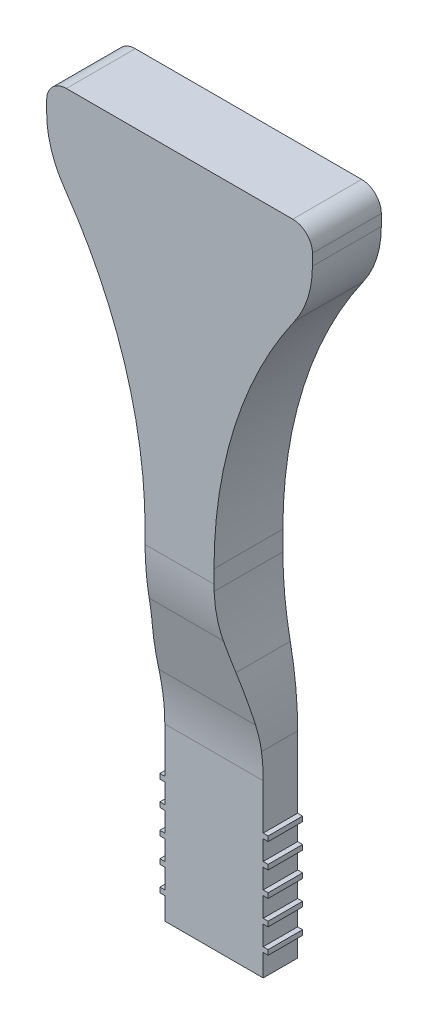
SolidWorks part; units mm, degrees
ref_plane "Front Plane" through (0, 0, 0) normal (0, 0, 1) x (1, 0, 0)
ref_plane "Top Plane" through (0, 0, 0) normal (0, 1, 0) x (1, 0, 0)
ref_plane "Right Plane" through (0, 0, 0) normal (1, 0, 0) x (0, 0, -1)
sketch "Sketch1" plane through (0, 0, 0) normal (0, 0, 1) x (1, 0, 0)
  line L0 (-4.25, -42.6429) -> (4.25, -42.6429) construction
  line L1 (-5, -50.1429) -> (-5, -70.1429)
  line L2 (-5, -70.1429) -> (5, -70.1429)
  line L3 (5, -70.1429) -> (5, -50.1429)
  line L5 (-13.5, -1.5201) -> (-13.5, -0.3772)
  line L6 (-11.5, 1.6228) -> (11.5, 1.6228)
  line L7 (13.5, -0.3772) -> (13.5, -1.5201)
  line L13 (3.5, -33.1429) -> (3.5, -35.1429)
  line L14 (3.5, -35.1429) -> (-3.5, -35.1429) construction
  line L15 (-3.5, -35.1429) -> (-3.5, -33.1429)
  line L22 (-3.5, -33.1429) -> (3.5, -33.1429) construction
  line L23 (-11.6818, -7.2697) -> (11.6818, -7.2697) construction
  line L24 (0, 3.6228) -> (0, -7.2697) construction
  line L25 (12.7, 3.6228) -> (-12.7, 3.6228) construction
  line L26 (-5, -50.1429) -> (5, -50.1429) construction
  line L27 (0, -35.1429) -> (0, -42.6429) construction
  line L28 (0, -42.6429) -> (0, -50.1429) construction
  arc A0 (-3.5, -35.1429) -> (-4.25, -42.6429) centre (-41.375, -35.1429) cw
  arc A1 (3.5, -35.1429) -> (4.25, -42.6429) centre (41.375, -35.1429) ccw
  arc A2 (11.7818, -7.1268) -> (3.7267, -29.625) centre (48.6, -33) ccw construction
  arc A3 (11.7818, -7.1268) -> (3.7267, -29.625) centre (48.6, -33) ccw construction
  arc A4 (-4.25, -42.6429) -> (-5, -50.1429) centre (32.875, -50.1429) ccw
  arc A5 (4.25, -42.6429) -> (5, -50.1429) centre (-32.875, -50.1429) cw
  arc A24 (13.5, -1.5201) -> (11.6818, -7.2697) centre (3.5, -1.5201) cw
  arc A25 (-13.5, -1.5201) -> (-11.6818, -7.2697) centre (-3.5, -1.5201) ccw
  arc A26 (-11.6818, -7.2697) -> (-3.5, -33.1429) centre (-48.5, -33.1429) cw
  arc A27 (11.6818, -7.2697) -> (3.5, -33.1429) centre (48.5, -33.1429) ccw
  arc A28 (11.5, 1.6228) -> (13.5, -0.3772) centre (11.5, -0.3772) cw
  arc A29 (-13.5, -0.3772) -> (-11.5, 1.6228) centre (-11.5, -0.3772) cw
  dimension "D1" = 10
  dimension "D2" = 45
  dimension "D4" = 2
  dimension "D10" = 15
  dimension "7" = 7
  dimension "D3" = 27
  dimension "D5" = 2
  dimension "D6" = 2
  dimension "D7" = 20
  dimension "D8" = 10
extrude "Boss-Extrude1" add sketch "Sketch1" along normal blind 7
sketch "Sketch4" plane through (0, 0, 0) normal (1, 0, 0) x (0, 0, -1)
  line L0 (-3.5, -70.1429) -> (-3.5, -50.1429)
  line L1 (-7, -70.1429) -> (0, -70.1429) construction
  line L2 (-3.5, -50.1429) -> (-7, -37.1429)
  line L4 (-7, -37.1429) -> (-7, -70.1429)
  line L5 (-7, -70.1429) -> (-3.5, -70.1429)
  line L6 (-7, -35.1429) -> (-7, -42.6429) construction
  point P6 (-7, -36.4438)
  point P9 (0, 0)
  point P12 (-3.5, -52.5516)
  dimension "D1" = 20
  dimension "D2" = 2
extrude "Cut-Extrude4" cut sketch "Sketch4" against normal through all both and the other way through all contours L2 L4 L5 L0
fillet "Fillet2" radius 20 2 edges at (0, -37.1429, 7) (0, -50.1429, 3.5)
sketch "Sketch5" plane through (-5, 0, 0) normal (-1, 0, 0) x (0, 0, 1)
  line L0 (0, -50.1429) -> (0, -70.1429) construction
  line L1 (0, -64.8929) -> (3.5, -64.8929)
  line L2 (0, -64.8929) -> (0, -65.3929)
  line L3 (0, -65.3929) -> (3.5, -65.3929)
  line L4 (3.5, -64.8929) -> (3.5, -65.3929)
  line L5 (3.5, -70.1429) -> (3.5, -52.7881) construction
  line L6 (0, -65.1429) -> (3.5, -65.1429) construction
  line L7 (0, -62.3929) -> (3.5, -62.3929)
  line L8 (0, -62.3929) -> (0, -62.8929)
  line L9 (0, -62.8929) -> (3.5, -62.8929)
  line L10 (3.5, -62.3929) -> (3.5, -62.8929)
  line L11 (0, -59.8929) -> (3.5, -59.8929)
  line L12 (0, -59.8929) -> (0, -60.3929)
  line L13 (0, -60.3929) -> (3.5, -60.3929)
  line L14 (3.5, -59.8929) -> (3.5, -60.3929)
  line L15 (3.5, -70.1429) -> (0, -70.1429) construction
  line L16 (0, -62.6429) -> (3.5, -62.6429) construction
  line L17 (0, -67.6429) -> (3.5, -67.6429) construction
  line L18 (0, -60.1429) -> (3.5, -60.1429) construction
  line L19 (0, -67.3929) -> (3.5, -67.3929)
  line L20 (0, -67.3929) -> (0, -67.8929)
  line L21 (0, -67.8929) -> (3.5, -67.8929)
  line L22 (3.5, -67.3929) -> (3.5, -67.8929)
  line L23 (0, -57.6429) -> (3.5, -57.6429) construction
  line L24 (0, -57.3929) -> (3.5, -57.3929)
  line L25 (0, -57.3929) -> (0, -57.8929)
  line L26 (0, -57.8929) -> (3.5, -57.8929)
  line L27 (3.5, -57.3929) -> (3.5, -57.8929)
  dimension "D1" = 5
  dimension "D2" = 7.5
  dimension "D3" = 10
  dimension "D4" = 0.5
  dimension "D5" = 2.5
  dimension "D6" = 12.5
extrude "Boss-Extrude2" add sketch "Sketch5" along normal blind 0.5
mirror "Mirror1" about plane through (0, 0, 0) normal (1, 0, 0) of "Boss-Extrude2"
